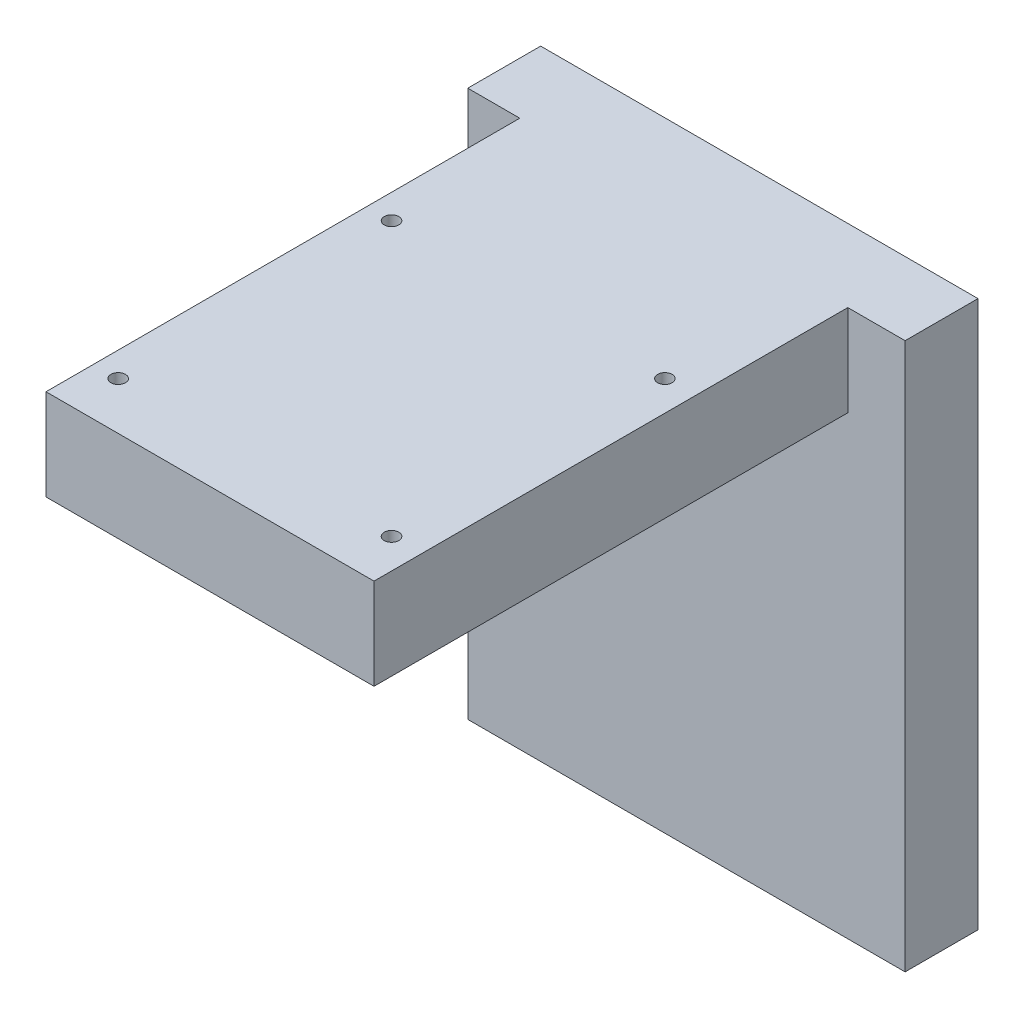
SolidWorks part; units mm, degrees
ref_plane "前视基准面" through (0, 0, 0) normal (0, 0, 1) x (1, 0, 0)
ref_plane "上视基准面" through (0, 0, 0) normal (0, 1, 0) x (1, 0, 0)
ref_plane "右视基准面" through (0, 0, 0) normal (1, 0, 0) x (0, 0, -1)
other "Configuration Table"
sketch "草图1" plane through (0, 0, 0) normal (0, 1, 0) x (1, 0, 0)
  line L1 (-72.5362, 19.5652) -> (47.4638, 19.5652)
  line L2 (-72.5362, 19.5652) -> (-72.5362, -0.4348)
  line L3 (-72.5362, -0.4348) -> (47.4638, -0.4348)
  line L4 (47.4638, 19.5652) -> (47.4638, -0.4348)
  dimension "D1" = 120
  dimension "D2" = 20
extrude "凸台-拉伸1" add sketch "草图1" along normal blind 150
sketch "草图2" plane through (0, 0, 0.4348) normal (0, 0, 1) x (1, 0, 0)
  line L0 (-72.5362, 150) -> (47.4638, 150) construction
  line L1 (-58.2615, 150) -> (31.7385, 150)
  line L2 (-58.2615, 150) -> (-58.2615, 125)
  line L3 (-58.2615, 125) -> (31.7385, 125)
  line L4 (31.7385, 150) -> (31.7385, 125)
  dimension "D1" = 25
  dimension "D2" = 90
extrude "凸台-拉伸2" add sketch "草图2" along normal blind 130 contours L2 L1 L4 L3
sketch "草图3" plane through (0, 150, 0) normal (0, 1, 0) x (1, 0, 0)
  circle A0 centre (-51.4924, -42.398) radius 2
  circle A1 centre (23.5076, -42.4005) radius 2
  circle A2 centre (-51.4924, -117.4005) radius 2
  circle A4 centre (23.5076, -117.4005) radius 2
  point P8 (-30.9989, -70.6468)
  point P9 (-19.8002, -43.8608)
  point P10 (-6.6342, -71.7061)
  point P11 (3.6564, -58.0861)
  point P12 (-32.4903, -58.0861)
  point P13 (8.4032, -93.7498)
  point P14 (6.9323, -60.4361)
  point P15 (-30.9989, -60.4361)
  point P16 (-30.9989, -93.7498)
  point P17 (8.7829, -93.7498)
  point P18 (-51.8787, -97.8361)
  point P19 (15.9595, -95.3336)
  point P20 (24.176, -96.7447)
  point P21 (0, 0)
  point P22 (24.176, -62.6749)
  point P23 (0, 0)
  point P24 (0, 0)
  point P25 (29.0848, -57.7634)
  point P26 (0, 0)
  point P27 (24.176, -127.2455)
  point P28 (-50.7624, -127.2455)
  point P29 (-50.7624, -87.5826)
  point P30 (24.2376, -87.5826)
  point P31 (0, 0)
  point P32 (0, 0)
  point P33 (0, 0)
  point P34 (-51.4924, -117.4031)
  point P35 (0, 0)
  dimension "D1" = 4
  dimension "D2" = 75
  dimension "D3" = 75
  dimension "D4" = 75
extrude "切除-拉伸1" cut sketch "草图3" against normal blind 130
sketch "草图5" plane through (0, 125, 0) normal (0, -1, 0) x (1, 0, 0)
  circle A0 centre (-51.4924, 117.4005) radius 5
  circle A1 centre (23.5076, 117.4005) radius 5
  circle A2 centre (23.5076, 42.4005) radius 5
  circle A3 centre (-51.4924, 42.398) radius 5
  dimension "D1" = 10
  dimension "D2" = 10
  dimension "D3" = 10
  dimension "D4" = 10
extrude "切除-拉伸2" cut sketch "草图5" against normal blind 17
